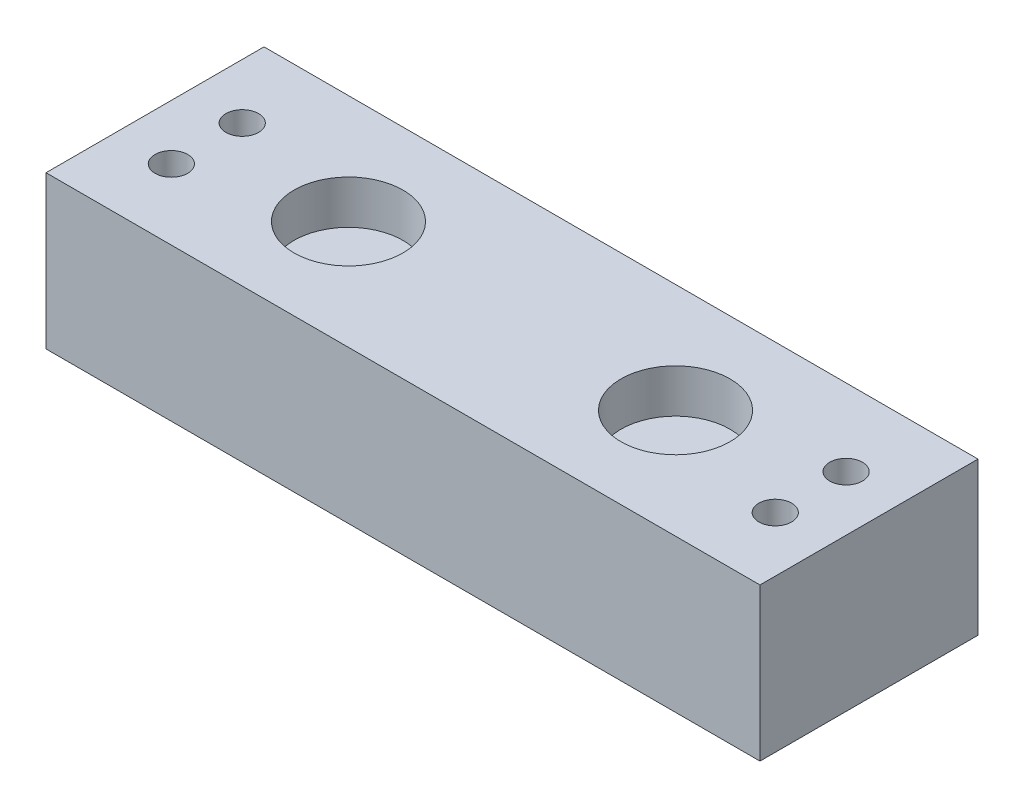
SolidWorks part; units mm, degrees
ref_plane "Płaszczyzna przednia" through (0, 0, 0) normal (0, 0, 1) x (1, 0, 0)
ref_plane "Płaszczyzna górna" through (0, 0, 0) normal (0, 1, 0) x (1, 0, 0)
ref_plane "Płaszczyzna prawa" through (0, 0, 0) normal (1, 0, 0) x (0, 0, -1)
sketch "Sketch1" plane through (0, 0, 0) normal (0, 0, 1) x (1, 0, 0)
  line L0 (26.75, 14) -> (26.75, 6)
  line L1 (0, 0) -> (65.5, 0)
  line L2 (0, 0) -> (0, 14)
  line L3 (0, 14) -> (26.75, 14)
  line L4 (65.5, 0) -> (65.5, 14)
  line L5 (26.75, 6) -> (38.75, 6)
  line L6 (38.75, 6) -> (38.75, 14)
  line L7 (38.75, 14) -> (65.5, 14)
  dimension "D1" = 65.5
  dimension "D2" = 14
  dimension "D3" = 26.75
  dimension "D4" = 26.75
  dimension "D5" = 8
extrude "Boss-Extrude1" add sketch "Sketch1" along normal blind 20
sketch "Sketch14" plane through (0, 0, 0) normal (0, 0, 1) x (1, 0, 0)
  line L1 (65.5, 0) -> (0, 0)
  line L2 (65.5, 0) -> (65.5, 14)
  line L3 (65.5, 14) -> (0, 14)
  line L4 (0, 0) -> (0, 14)
  line L5 (65.5, 0) -> (0, 14) construction
  line L6 (65.5, 14) -> (0, 0) construction
  point P4 (32.75, 7)
extrude "Boss-Extrude2" add sketch "Sketch14" along normal blind 20
sketch "Sketch12" plane through (0, 14, 0) normal (0, 1, 0) x (1, 0, 0)
  line L0 (65.5, 0) -> (0, 0) construction
  line L2 (32.75, -20) -> (32.75, -1.1988) construction
  line L3 (38.75, -20) -> (26.75, -20) construction
  circle A0 centre (17.75, -10) radius 5
  circle A1 centre (47.75, -10) radius 5
  dimension "D1" = 10
  dimension "D2" = 10
hole_wizard "Ø3.2 (3.2) Diameter Hole1" positions "Sketch8" profile "Sketch9" hole size "Ø3.2" standard "ANSI Metric"
sketch "Sketch8" plane through (0, 0, 0) normal (0, 1, 0) x (1, 0, 0)
  point P0 (32.75, -10)
sketch "Sketch9" plane through (32.75, 0, 10) normal (1, 0, 0) x (0, 0, -1)
  line L0 (0, 0) -> (0, 12.9614)
  line L1 (0, 12.9614) -> (1.6, 12)
  line L2 (1.6, 12) -> (1.6, 0)
  line L5 (1.6, 0) -> (0, 0)
  line L10 (0, 12.9614) -> (-1.6, 12) construction
  line L11 (0, -6.35) -> (0, 107.95) construction
  dimension "Hole Dia." = 3.2
  dimension "Hole Depth" = 12
  dimension "Drill Angle" = 118
sketch "Sketch13" plane through (0, 0, 0) normal (0, -1, 0) x (1, 0, 0)
  circle A0 centre (5.05, 7.05) radius 1.5
  circle A1 centre (5.05, 13.55) radius 1.5
  circle A2 centre (60.45, 7.05) radius 1.5
  circle A3 centre (60.45, 13.55) radius 1.5
extrude "Cut-Extrude2" cut sketch "Sketch13" against normal blind 54
extrude "Cut-Extrude3" cut sketch "Sketch12" against normal blind 4
